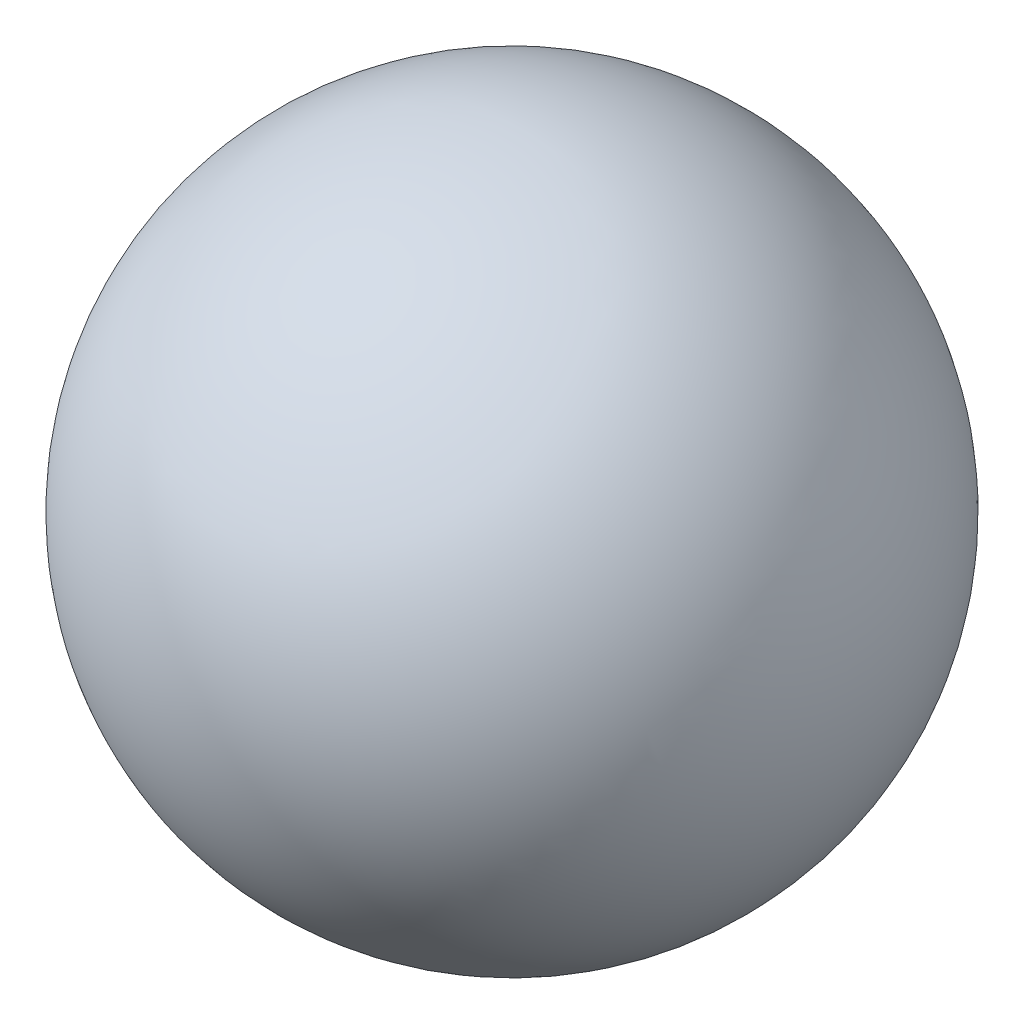
SolidWorks part; units mm, degrees
ref_plane "前视基准面" through (0, 0, 0) normal (0, 0, 1) x (1, 0, 0)
ref_plane "上视基准面" through (0, 0, 0) normal (0, 1, 0) x (1, 0, 0)
ref_plane "右视基准面" through (0, 0, 0) normal (1, 0, 0) x (0, 0, -1)
sketch "草图1" plane through (0, 0, 0) normal (0, 1, 0) x (1, 0, 0)
  line L0 (0, 16.7477) -> (0, -19.1609) construction
  line L1 (0, 10) -> (0, -10)
  arc A0 (0, -10) -> (0, 10) centre (0, 0) ccw
  dimension "D1" = 20
revolve "旋转1" add sketch "草图1" angle 360 about L0
sketch "草图2" plane through (0, 0, 0) normal (0, 1, 0) x (1, 0, 0)
  circle A0 centre (0, 0) radius 2.5
  dimension "D1" = 5
extrude "切除-拉伸1" cut sketch "草图2" against normal through all
sketch "草图3" plane through (0, 0, 0) normal (1, 0, 0) x (0, 0, -1)
  circle A0 centre (0, 0) radius 2.5
  dimension "D1" = 5
extrude "切除-拉伸2" cut sketch "草图3" against normal through all
sketch "草图4" plane through (0, 0, 0) normal (0, 0, 1) x (1, 0, 0)
  circle A0 centre (0, 0) radius 2.5
  dimension "D1" = 5
extrude "切除-拉伸3" cut sketch "草图4" against normal through all
